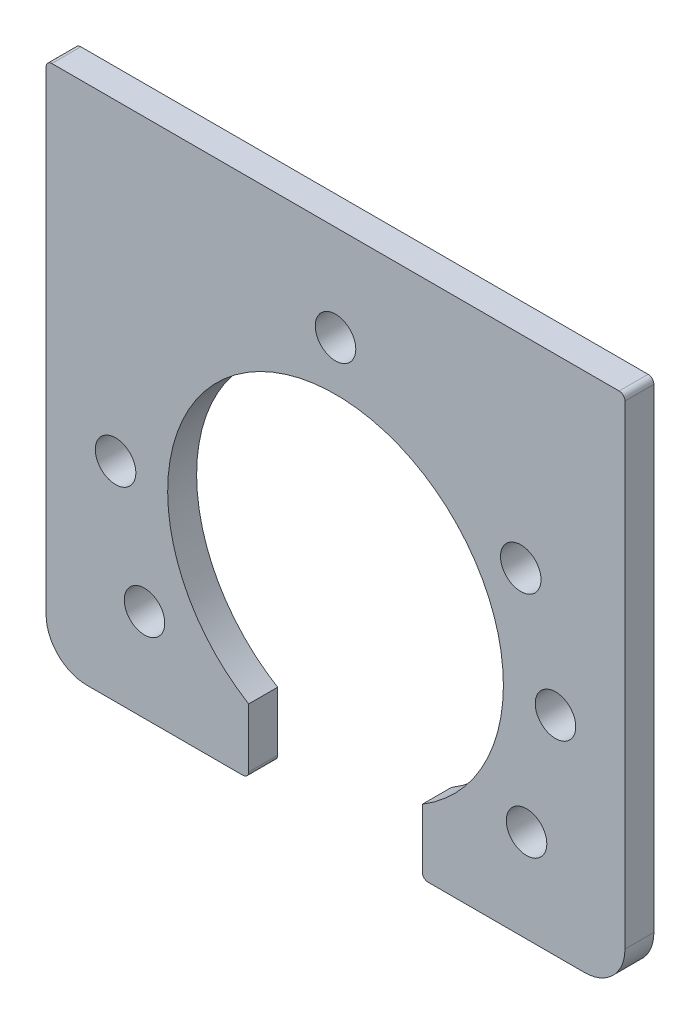
SolidWorks part; units mm, degrees
ref_plane "Front Plane" through (0, 0, 0) normal (0, 0, 1) x (1, 0, 0)
ref_plane "Top Plane" through (0, 0, 0) normal (0, 1, 0) x (1, 0, 0)
ref_plane "Right Plane" through (0, 0, 0) normal (1, 0, 0) x (0, 0, -1)
sketch "Sketch1" plane through (0, 0, 0) normal (0, 0, 1) x (1, 0, 0)
  line L0 (0, 0) -> (-100, 0)
  line L2 (0, -80) -> (0, -83)
  line L3 (-92, -90) -> (-93, -90)
  line L4 (-100, -80) -> (-100, -83)
  line L6 (-65, -90) -> (-92, -90)
  line L7 (-35, -90) -> (-8, -90)
  line L9 (0, 0) -> (0, -80)
  line L10 (-8, -90) -> (-7, -90)
  line L11 (-100, 0) -> (-100, -80)
  line L15 (-65, -78.8193) -> (-65, -90)
  line L16 (-35, -78.8193) -> (-35, -90)
  circle A0 centre (-50, -16.5) radius 3.5
  circle A1 centre (-12, -54) radius 3.5
  arc A2 (-7, -90) -> (0, -83) centre (-7, -83) ccw
  circle A3 centre (-17, -74) radius 3.5
  arc A4 (-93, -90) -> (-100, -83) centre (-93, -83) cw
  circle A5 centre (-18, -35) radius 3.5
  circle A6 centre (-83, -74) radius 3.5
  circle A7 centre (-88, -54) radius 3.5
  arc A8 (-35, -78.8193) -> (-65, -78.8193) centre (-50, -54) ccw
  dimension "D2" = 35
extrude "Boss-Extrude1" add sketch "Sketch1" along normal blind 5
fillet "Fillet1" radius 1 1 edges at (-100, 0, 2.5)
fillet "Fillet2" radius 1 1 edges at (0, 0, 2.5)
fillet "Fillet3" radius 1 1 edges at (-65, -90, 2.5)
fillet "Fillet4" radius 1 1 edges at (-35, -90, 2.5)
